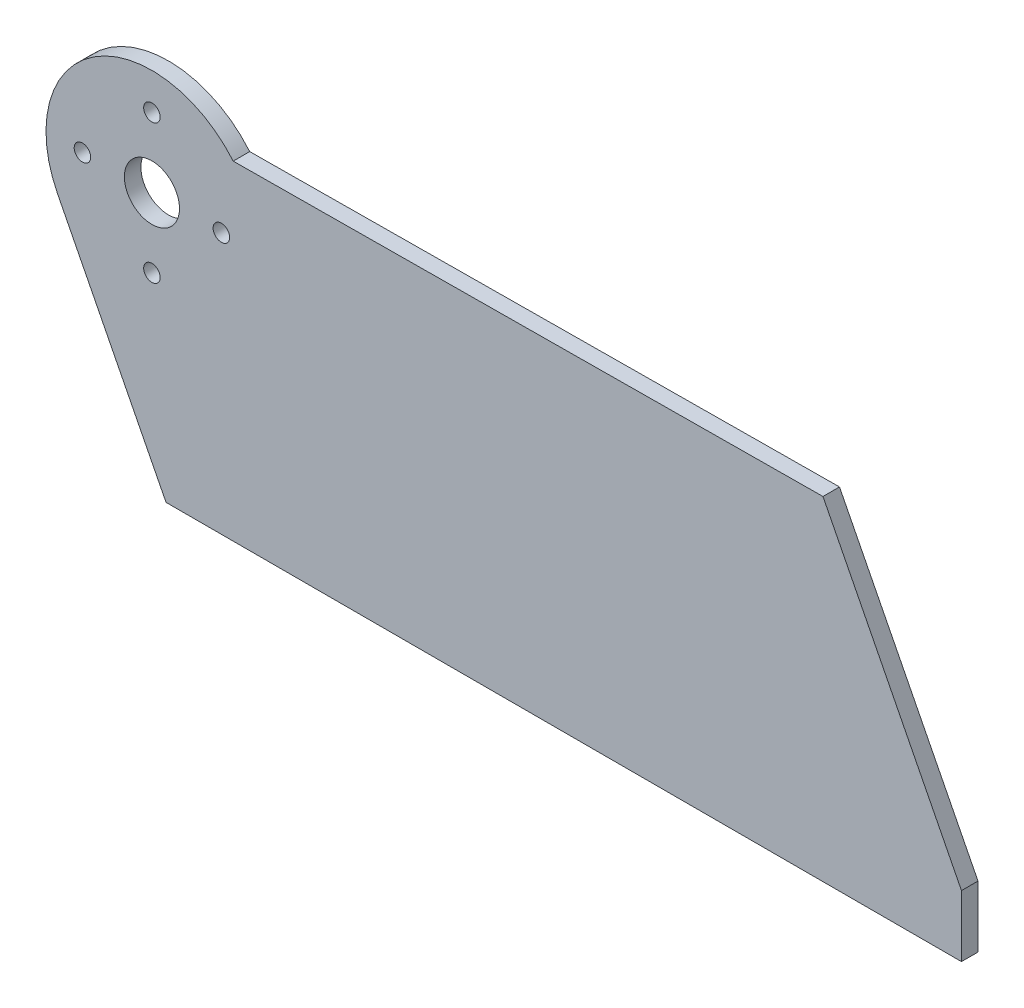
SolidWorks part; units mm, degrees
ref_plane "Front Plane" through (0, 0, 0) normal (0, 0, 1) x (1, 0, 0)
ref_plane "Top Plane" through (0, 0, 0) normal (0, 1, 0) x (1, 0, 0)
ref_plane "Right Plane" through (0, 0, 0) normal (1, 0, 0) x (0, 0, -1)
sketch "Sketch1" plane through (0, 0, 0) normal (0, 0, 1) x (1, 0, 0)
  line L0 (121.8153, 13.1449) -> (146.9594, -36.242)
  line L1 (2.5617, -47.4117) -> (146.9594, -47.4117)
  line L2 (146.9594, -47.4117) -> (146.9594, -36.242)
  line L3 (121.8153, 13.1449) -> (14.7532, 12.3338)
  line L4 (-17.1362, -8.7252) -> (2.5617, -47.4117)
  circle A0 centre (0, 0) radius 5
  circle A1 centre (0, 0) radius 12.6095 construction
  arc A2 (14.7532, 12.3338) -> (-17.1362, -8.7252) centre (0, 0) ccw
  circle A3 centre (12.6095, 0) radius 1.5
  circle A4 centre (0, -12.6095) radius 1.5
  circle A5 centre (-12.6095, 0) radius 1.5
  circle A6 centre (0, 12.6095) radius 1.5
  dimension "D1" = 25.219
  dimension "D2" = 10
  dimension "D3" = 3
  dimension "D4" = 4
extrude "Boss-Extrude1" add sketch "Sketch1" along normal blind 3
